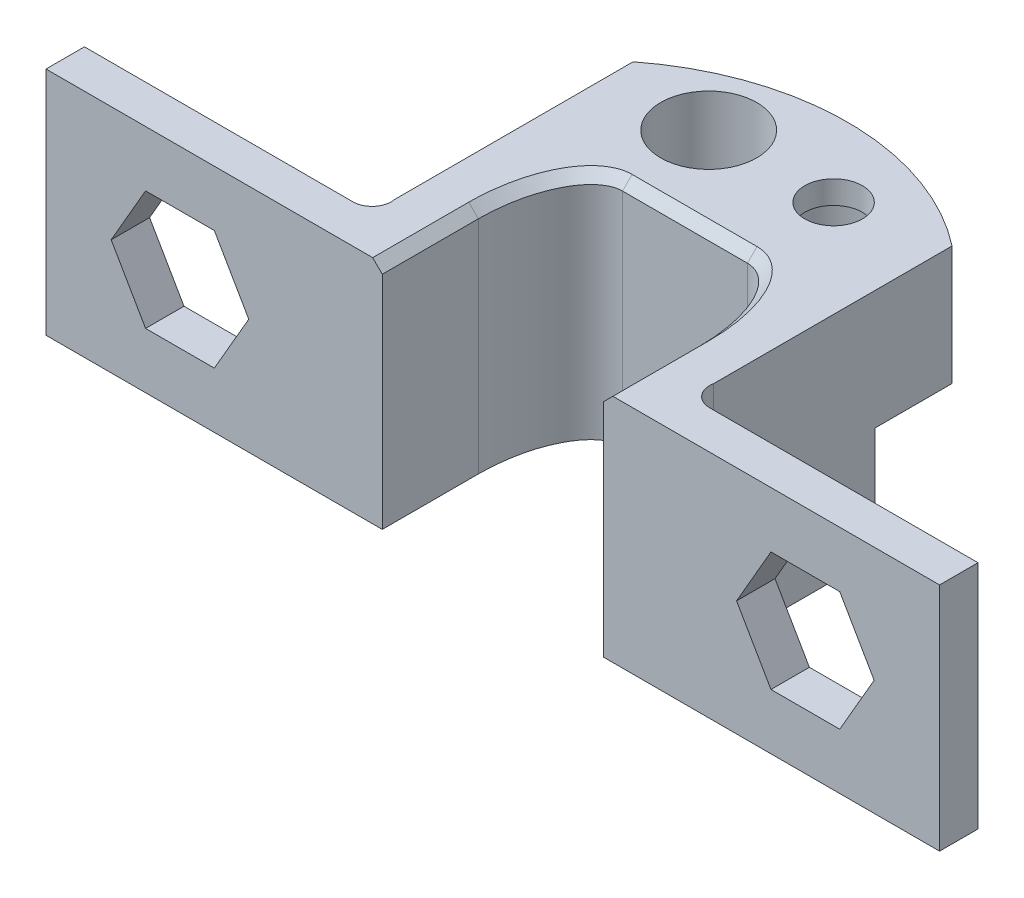
SolidWorks part; units mm, degrees
ref_plane "Front Plane" through (0, 0, 0) normal (0, 0, 1) x (1, 0, 0)
ref_plane "Top Plane" through (0, 0, 0) normal (0, 1, 0) x (1, 0, 0)
ref_plane "Right Plane" through (0, 0, 0) normal (1, 0, 0) x (0, 0, -1)
sketch "Sketch1" plane through (0, 0, 0) normal (0, 1, 0) x (1, 0, 0)
  line L0 (-3.25, -5) -> (-23.25, -5)
  line L1 (-3.25, -5) -> (3.25, -5) construction
  line L2 (-3.25, -5) -> (-3.25, 5) construction
  line L3 (-3.25, 5) -> (3.25, 5)
  line L4 (3.25, -5) -> (3.25, 5) construction
  line L5 (-3.25, -5) -> (3.25, 5) construction
  line L6 (-3.25, 5) -> (3.25, -5) construction
  line L7 (-23.25, -5) -> (-23.25, -3)
  line L8 (-23.25, -3) -> (-9.2822, -3)
  line L9 (3.25, -5) -> (23.25, -5)
  line L10 (23.25, -5) -> (23.25, -3)
  line L11 (23.25, -3) -> (9.2822, -3)
  line L12 (-8.3, -1.8121) -> (-8.3, 6.6)
  line L13 (-8.3, 6.6) -> (8.3, 6.6)
  line L14 (8.3, -1.8119) -> (8.3, 6.6)
  line L15 (-5.7498, 0) -> (-5.7498, -5)
  line L16 (5.7487, 0) -> (5.7487, -5)
  arc A0 (-9.2822, -3) -> (-8.3, -1.8121) centre (-9.2822, -2) ccw
  arc A1 (9.2822, -3) -> (8.3, -1.8119) centre (9.2822, -2) cw
  ellipse E0 centre (-3.25, 0) end of major axis (-3.25, 5) minor radius 2.4998 (-3.25, 5) -> (-3.25, -5) ccw
  ellipse E1 centre (3.25, 0) end of major axis (3.25, 5) minor radius 2.4987 (3.25, -5) -> (3.25, 5) ccw
  point P0 (0, 0)
  dimension "D6" = 1
  dimension "D7" = 1
  dimension "D1" = 6.5
  dimension "D2" = 10
  dimension "D3" = 20
  dimension "D4" = 2
  dimension "D5" = 20
  dimension "D8" = 16.6
  dimension "D9" = 1.6
  dimension "D10" = 5.05
  dimension "D11" = 5.05
extrude "Boss-Extrude1" add sketch "Sketch1" along normal blind 12
sketch "Sketch2" plane through (0, 0, 3) normal (0, 0, -1) x (-1, 0, 0)
  line L0 (-23.25, 12) -> (-9.2822, 0) construction
  line L1 (-23.25, 0) -> (-9.2822, 12) construction
  line L2 (23.25, 12) -> (9.3079, 0) construction
  line L3 (23.25, 0) -> (9.2822, 0) construction
  line L4 (23.25, 0) -> (9.2822, 12) construction
  line L5 (-16.2661, 6) -> (-16.2661, -2.9743) construction
  line L6 (-16.2661, -0.7517) -> (-16.2661, 3) construction
  line L10 (16.2789, 6) -> (16.2789, -2.9743) construction
  line L11 (19.8585, 6) -> (18.0687, 9.1)
  line L12 (-12.6865, 6) -> (-14.4763, 9.1)
  line L13 (-14.4763, 9.1) -> (-18.0559, 9.1)
  line L14 (-18.0559, 9.1) -> (-19.8457, 6)
  line L15 (-19.8457, 6) -> (-18.0559, 2.9)
  line L16 (18.0687, 9.1) -> (14.4891, 9.1)
  line L17 (14.4891, 9.1) -> (12.6994, 6)
  line L18 (-18.0559, 2.9) -> (-14.4763, 2.9)
  line L19 (-14.4763, 2.9) -> (-12.6865, 6)
  line L20 (12.6994, 6) -> (14.4891, 2.9)
  line L21 (14.4891, 2.9) -> (18.0687, 2.9)
  line L22 (18.0687, 2.9) -> (19.8585, 6)
  circle A0 centre (-16.2661, 6) radius 3.1 construction
  circle A1 centre (16.2789, 6) radius 3.1 construction
  point P32 (11.4039, 0.6926)
  dimension "D1" = 6.2
  dimension "D2" = 6.2
extrude "Cut-Extrude1" cut sketch "Sketch2" against normal blind 10
sketch "Sketch3" plane through (0, 12, 0) normal (0, 1, 0) x (1, 0, 0)
  line L0 (-3.25, 5) -> (-3.25, 12.9854) construction
  line L1 (3.25, 5) -> (3.25, 12.9854) construction
  line L2 (-8.3, 6.6) -> (8.3, 6.6)
  line L3 (-8.1382, 9.4853) -> (3.25, 9.4853) construction
  line L4 (8.3, 6.6) -> (8.3, 10.6)
  line L5 (-8.3, 6.6) -> (-8.3, 10.6)
  circle A0 centre (-3.25, 9.4853) radius 2.5
  circle A1 centre (3.25, 9.4853) radius 2.5 construction
  circle A2 centre (3.25, 9.4853) radius 1.5
  circle A3 centre (0, 0) radius 13.8 construction
  circle A4 centre (-3.25, 9.4853) radius 2.85 construction
  circle A5 centre (3.25, 9.4853) radius 2.85 construction
  arc A6 (8.3, 10.6) -> (-8.3, 10.6) centre (0, 0) ccw
  circle A7 centre (0, 0) radius 13 construction
  ellipse E5 centre (-3.5001, 0.0027) end of major axis (-3.5004, -7) minor radius 5 (-3.1436, 6.9875) -> (-3.5619, 7.0048) ccw
  dimension "D1" = 5
  dimension "D2" = 3
  dimension "D3" = 27.6
  dimension "D4" = 5.7
  dimension "D5" = 5.7
  dimension "D8" = 13.4629
  dimension "D9" = 26
  dimension "D6" = 4
  dimension "D7" = 4
extrude "Boss-Extrude2" add sketch "Sketch3" against normal blind 1.2
sketch "Sketch4" plane through (0, 10.8, 0) normal (0, -1, 0) x (1, 0, 0)
  line L0 (-8.3, -6.6) -> (8.3, -6.6)
  line L1 (8.3, -6.6) -> (8.3, -10.6)
  line L2 (-8.3, -6.6) -> (-8.3, -10.6)
  line L3 (-3.25, -9.4853) -> (3.25, -9.4853) construction
  line L4 (0, -7.2638) -> (0, -12.3361) construction
  circle A0 centre (-3.25, -9.4853) radius 2.5
  circle A1 centre (3.25, -9.4853) radius 2.5
  ellipse E1 centre (0, -10.6) end of major axis (8.3, -10.6) minor radius 3.3362 (-8.3, -10.6) -> (8.3, -10.6) ccw
  dimension "D1" = 5
  dimension "D2" = 5
extrude "Boss-Extrude3" add sketch "Sketch4" along normal blind 5
chamfer "Chamfer1" distance 0.5 angle 45 5 edges at (0, 12, -5) (-5.0176, 12, -3.5355) (5.0168, 12, -3.5355) (-5.7498, 12, 2.5) (5.7487, 12, 2.5)
